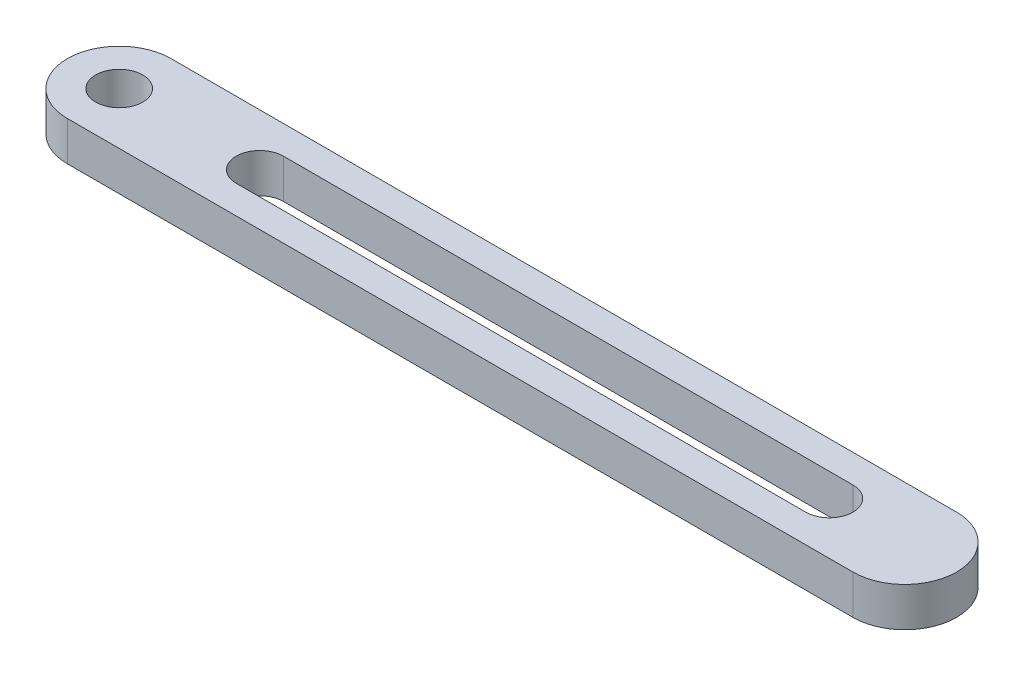
SolidWorks part; units mm, degrees
ref_plane "Front Plane" through (0, 0, 0) normal (0, 0, 1) x (1, 0, 0)
ref_plane "Top Plane" through (0, 0, 0) normal (0, 1, 0) x (1, 0, 0)
ref_plane "Right Plane" through (0, 0, 0) normal (1, 0, 0) x (0, 0, -1)
sketch "Sketch1" plane through (0, 0, 0) normal (0, 1, 0) x (1, 0, 0)
  line L0 (0, 0) -> (254, 0)
  line L1 (0, 0) -> (254, 0) construction
  line L2 (0, 16.764) -> (254, 16.764)
  line L3 (0, -16.764) -> (254, -16.764)
  arc A0 (0, 16.764) -> (0, -16.764) centre (0, 0) ccw
  arc A1 (254, -16.764) -> (254, 16.764) centre (254, 0) ccw
  circle A2 centre (0, 0) radius 7.62
  point P3 (127, 0)
  dimension "D2" = 16.764
  dimension "D1" = 254
extrude "Boss-Extrude1" add sketch "Sketch1" along normal blind 12.7
ref_plane "Plane1" through (0, 12.7, -16.764) normal (-1, 0, 0) x (0, 0, 1)
sketch "Sketch3" plane through (0, 12.7, 0) normal (0, 1, 0) x (1, 0, 0)
  line L0 (7.62, 0) -> (16.764, 0)
  line L1 (0, 16.764) -> (45.466, 16.764)
  line L2 (0, 27.0725) -> (0, 6.4555) construction
  line L3 (0, 16.764) -> (254, 16.764) construction
  line L6 (45.466, 7.62) -> (167.8985, 7.62)
  line L7 (45.466, -7.62) -> (102.616, -7.62)
  line L8 (167.8985, 7.62) -> (229.616, 7.62)
  line L9 (102.616, -7.62) -> (229.616, -7.62)
  circle A0 centre (254, 0) radius 16.764
  circle A1 centre (0, 0) radius 7.62
  arc A2 (0, 16.764) -> (0, -16.764) centre (0, 0) ccw construction
  circle A3 centre (0, 0) radius 16.764
  arc A7 (45.466, 7.62) -> (45.466, -7.62) centre (45.466, 0) ccw
  arc A10 (229.616, -7.62) -> (229.616, 7.62) centre (229.616, 0) ccw
  dimension "D3" = 33.528
  dimension "D1" = 45.466
extrude "Cut-Extrude1" cut sketch "Sketch3" against normal blind 45.974 contours A7 L7 L9 A10 L8 L6
